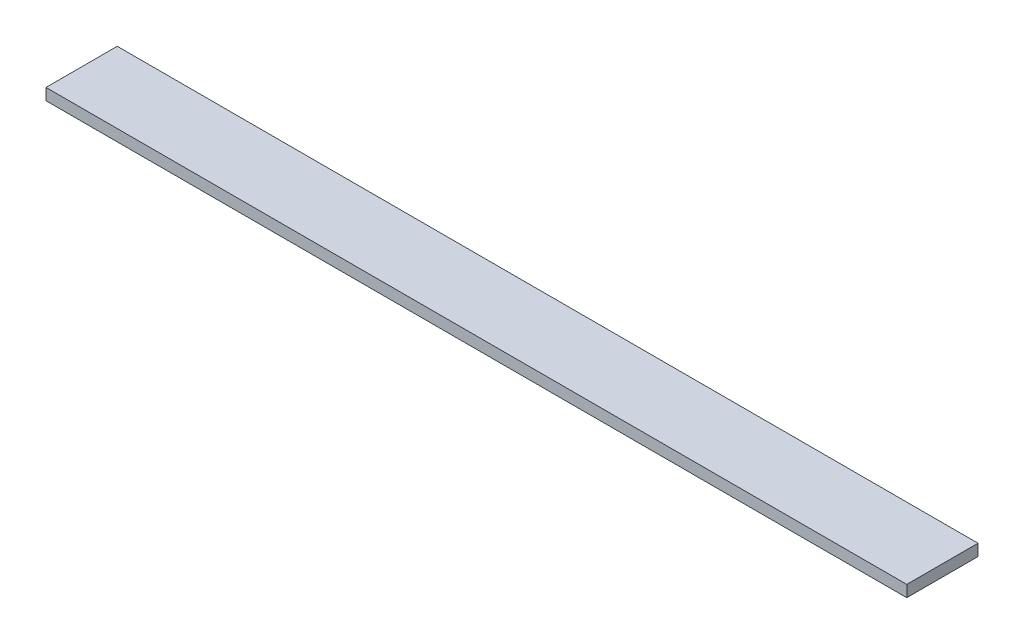
SolidWorks part; units mm, degrees
material "Pine"
ref_plane "Front Plane" through (0, 0, 0) normal (0, 0, 1) x (1, 0, 0)
ref_plane "Top Plane" through (0, 0, 0) normal (0, 1, 0) x (1, 0, 0)
ref_plane "Right Plane" through (0, 0, 0) normal (1, 0, 0) x (0, 0, -1)
sketch "Sketch1" plane through (0, 0, 0) normal (0, 1, 0) x (1, 0, 0)
  line L1 (-721.1739, 422.0587) -> (2117.2761, 422.0587)
  line L2 (-721.1739, 422.0587) -> (-721.1739, 187.1087)
  line L3 (-721.1739, 187.1087) -> (2117.2761, 187.1087)
  line L4 (2117.2761, 422.0587) -> (2117.2761, 187.1087)
  dimension "D1" = 234.95
  dimension "D2" = 2838.45
extrude "Boss-Extrude1" add sketch "Sketch1" along normal blind 38.1 contours L1 L4 L3 L2
